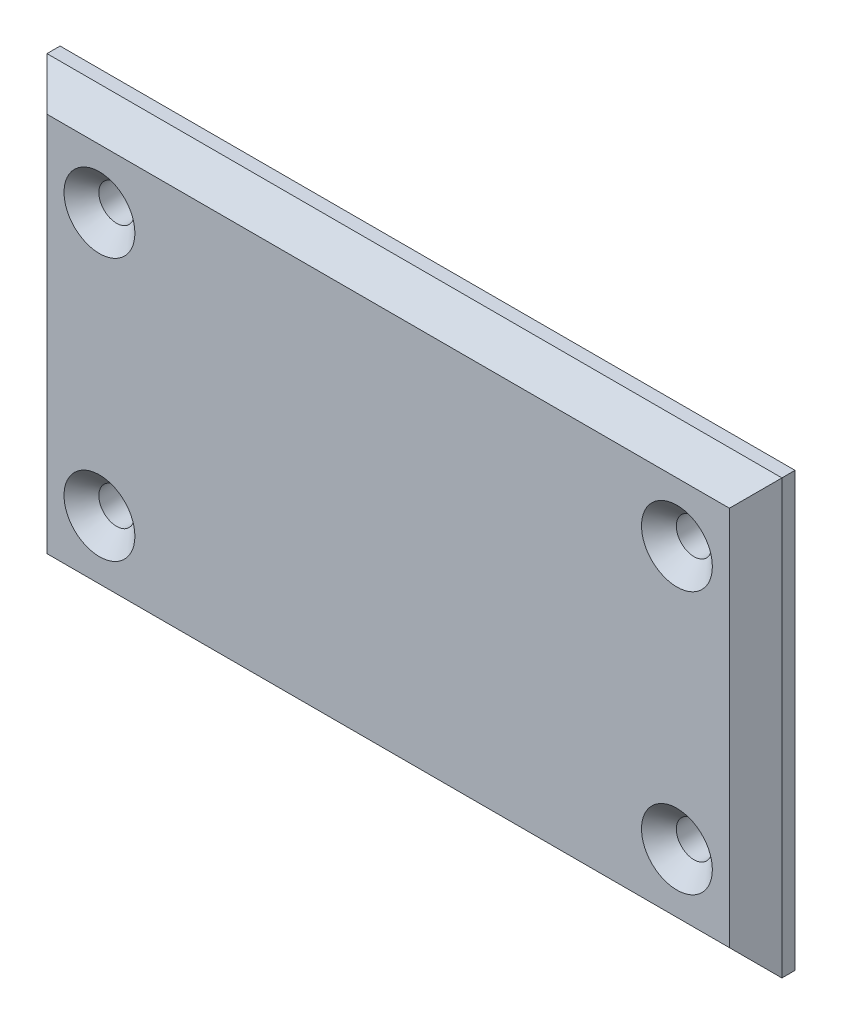
SolidWorks part; units mm, degrees
material "尼龙 6/10"
ref_plane "前视基准面" through (0, 0, 0) normal (0, 0, 1) x (1, 0, 0)
ref_plane "上视基准面" through (0, 0, 0) normal (0, 1, 0) x (1, 0, 0)
ref_plane "右视基准面" through (0, 0, 0) normal (1, 0, 0) x (0, 0, -1)
sketch "草图1" plane through (0, 0, 0) normal (0, 0, 1) x (1, 0, 0)
  line L1 (-140, 82.5) -> (140, 82.5)
  line L2 (-140, 82.5) -> (-140, -82.5)
  line L3 (-140, -82.5) -> (140, -82.5)
  line L4 (140, 82.5) -> (140, -82.5)
  line L5 (-140, 82.5) -> (140, -82.5) construction
  line L6 (-140, -82.5) -> (140, 82.5) construction
  point P0 (0, 0)
  dimension "D1" = 280
  dimension "D2" = 165
extrude "凸台-拉伸1" add sketch "草图1" along normal blind 15
chamfer "倒角1" distance 10 angle 45 4 edges at (0, 82.5, 15) (140, 0, 15) (0, -82.5, 15) (-140, 0, 15)
sketch "草图2" plane through (0, 0, 15) normal (0, 0, 1) x (1, 0, 0)
  line L0 (0, 0) -> (0, 98.4106) construction
  line L1 (0, 0) -> (159.2664, 0) construction
  point P3 (-110, 50)
  point P5 (110, 50)
  point P6 (110, -50)
  point P7 (-110, -50)
  dimension "D1" = 220
  dimension "D2" = 100
hole_wizard "打孔尺寸(%根据)内六角花形沉头螺钉的类型1" positions "草图3" profile "草图4" countersink size "M12" standard "GB"
sketch "草图3" plane through (0, 0, 15) normal (0, 0, 1) x (1, 0, 0)
  point P0 (-110, 50)
  point P3 (110, 50)
  point P5 (110, -50)
  point P8 (-110, -50)
sketch "草图4" plane through (-110, 50, 15) normal (1, 0, 0) x (0, -1, 0)
  line L0 (0, 0) -> (0, 24.0558)
  line L1 (0, 24.0558) -> (6.75, 20)
  line L2 (6.75, 20) -> (6.75, 6.5184)
  line L3 (6.75, 6.5184) -> (13.5, 0)
  line L5 (13.5, 0) -> (0, 0)
  line L6 (-6.75, 6.5184) -> (-13.5, 0) construction
  line L10 (0, 24.0558) -> (-6.75, 20) construction
  line L11 (0, -6.35) -> (0, 107.95) construction
  dimension "孔直径" = 13.5
  dimension "孔深度" = 20
  dimension "近端锥形沉头孔直径" = 27
  dimension "近端锥形沉头孔角度" = 92
  dimension "导头角度" = 118
